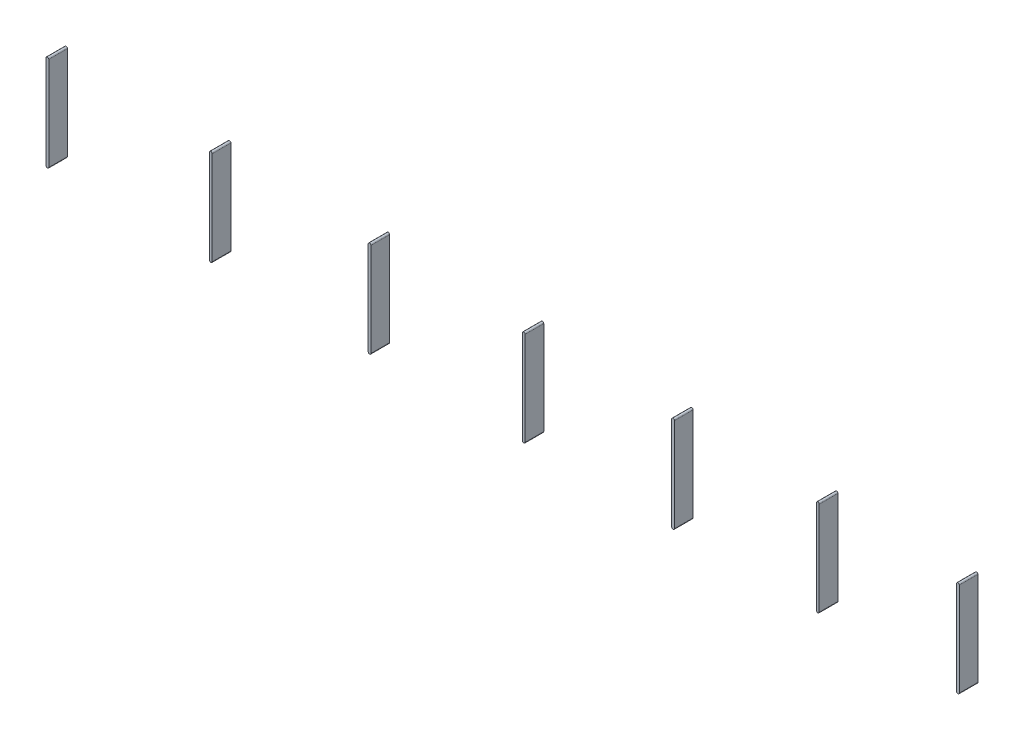
SolidWorks part; units mm, degrees
ref_plane "Front Plane" through (0, 0, 0) normal (0, 0, 1) x (1, 0, 0)
ref_plane "Top Plane" through (0, 0, 0) normal (0, 1, 0) x (1, 0, 0)
ref_plane "Right Plane" through (0, 0, 0) normal (1, 0, 0) x (0, 0, -1)
sketch "Sketch1" plane through (0, 0, 0) normal (0, 0, 1) x (1, 0, 0)
  line L0 (0, 0) -> (0, -20) construction
  line L1 (0.3, 0) -> (0.3, -20)
  line L2 (-0.3, 0) -> (-0.3, -20)
  line L3 (61, 0) -> (61, -20) construction
  line L4 (61.3, 0) -> (61.3, -20)
  line L5 (60.7, 0) -> (60.7, -20)
  line L6 (31, 0) -> (31, -20) construction
  line L7 (31.3, 0) -> (31.3, -20)
  line L8 (30.7, 0) -> (30.7, -20)
  line L9 (-32, 0) -> (-32, -20) construction
  line L10 (-31.7, 0) -> (-31.7, -20)
  line L11 (-32.3, 0) -> (-32.3, -20)
  line L12 (-65, 0) -> (-65, -20) construction
  line L13 (-64.7, 0) -> (-64.7, -20)
  line L14 (-65.3, 0) -> (-65.3, -20)
  line L15 (-99, 0) -> (-99, -20) construction
  line L16 (-98.7, 0) -> (-98.7, -20)
  line L17 (-99.3, 0) -> (-99.3, -20)
  line L18 (-134, 0) -> (-134, -20) construction
  line L19 (-133.7, 0) -> (-133.7, -20)
  line L20 (-134.3, 0) -> (-134.3, -20)
  line L21 (-134, -20) -> (-99, -20) construction
  line L22 (-99, -20) -> (-65, -20) construction
  line L23 (-65, -20) -> (-32, -20) construction
  line L24 (-32, -20) -> (0, -20) construction
  line L25 (0, -20) -> (31, -20) construction
  line L26 (31, -20) -> (61, -20) construction
  line L27 (61.3, -20) -> (62.3, -20) construction
  arc A0 (0.3, 0) -> (-0.3, 0) centre (0, 0) ccw
  arc A1 (-0.3, -20) -> (0.3, -20) centre (0, -20) ccw
  arc A2 (61.3, 0) -> (60.7, 0) centre (61, 0) ccw
  arc A3 (60.7, -20) -> (61.3, -20) centre (61, -20) ccw
  arc A4 (31.3, 0) -> (30.7, 0) centre (31, 0) ccw
  arc A5 (30.7, -20) -> (31.3, -20) centre (31, -20) ccw
  arc A6 (-31.7, 0) -> (-32.3, 0) centre (-32, 0) ccw
  arc A7 (-32.3, -20) -> (-31.7, -20) centre (-32, -20) ccw
  arc A8 (-64.7, 0) -> (-65.3, 0) centre (-65, 0) ccw
  arc A9 (-65.3, -20) -> (-64.7, -20) centre (-65, -20) ccw
  arc A10 (-98.7, 0) -> (-99.3, 0) centre (-99, 0) ccw
  arc A11 (-99.3, -20) -> (-98.7, -20) centre (-99, -20) ccw
  arc A12 (-133.7, 0) -> (-134.3, 0) centre (-134, 0) ccw
  arc A13 (-134.3, -20) -> (-133.7, -20) centre (-134, -20) ccw
  point P3 (0, -10)
  point P10 (61, -10)
  point P17 (31, -10)
  point P24 (-32, -10)
  point P31 (-65, -10)
  point P38 (-99, -10)
  point P45 (-134, -10)
  dimension "D9" = 0.3
  dimension "D2" = 35
  dimension "D1" = 1
  dimension "D3" = 34
  dimension "D4" = 33
  dimension "D5" = 32
  dimension "D6" = 31
  dimension "D7" = 30
  dimension "D8" = 20
extrude "Boss-Extrude1" add sketch "Sketch1" along normal blind 4
equation "\"D4@Sketch1\"=\"D3@Sketch1\"-\"D1@Sketch1\""
equation "\"D5@Sketch1\"=\"D4@Sketch1\"-\"D1@Sketch1\""
equation "\"D6@Sketch1\"=\"D5@Sketch1\"-\"D1@Sketch1\""
equation "\"D7@Sketch1\"=\"D6@Sketch1\"-\"D1@Sketch1\""
equation "\"D3@Sketch1\"=\"D2@Sketch1\"-\"D1@Sketch1\""
